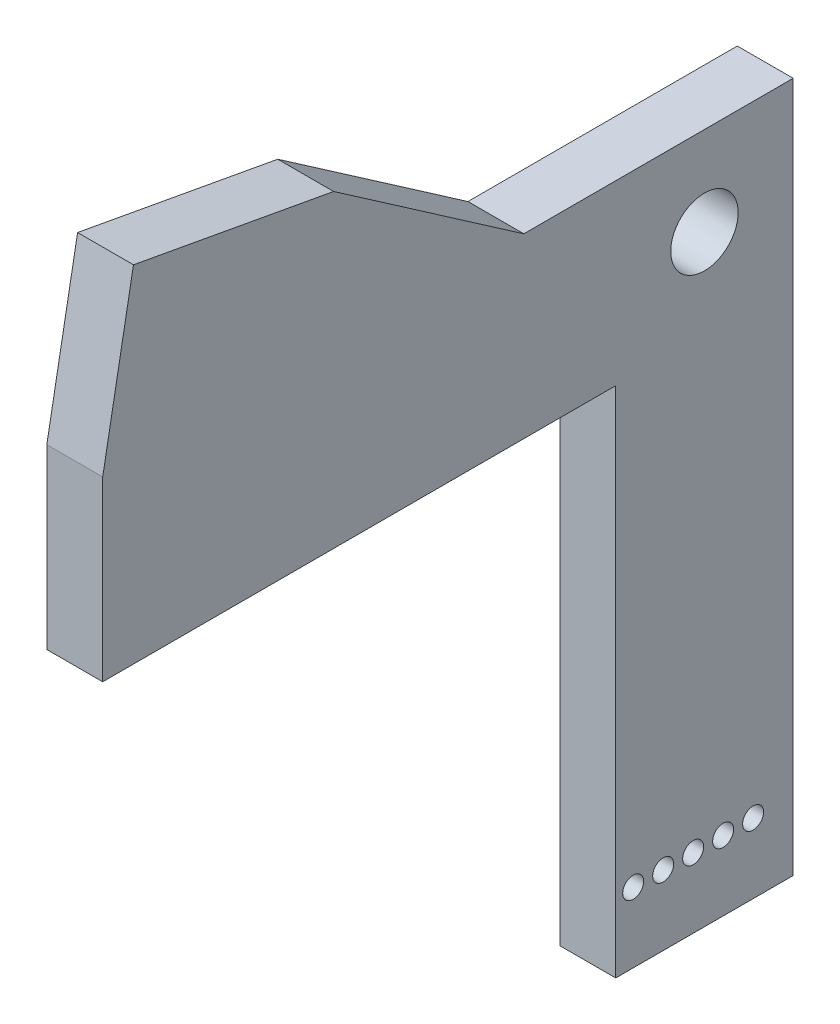
SolidWorks part; units mm, degrees
material "Hardboard"
ref_plane "Front Plane" through (0, 0, 0) normal (0, 0, 1) x (1, 0, 0)
ref_plane "Top Plane" through (0, 0, 0) normal (0, 1, 0) x (1, 0, 0)
ref_plane "Right Plane" through (0, 0, 0) normal (1, 0, 0) x (0, 0, -1)
sketch "Sketch1" plane through (0, 0, 0) normal (1, 0, 0) x (0, 0, -1)
  line L0 (-43.0661, 6.35) -> (6.35, 6.35)
  line L1 (6.35, 6.35) -> (6.35, -43.0661)
  line L2 (6.35, -43.0661) -> (-6.35, -43.0661)
  line L3 (-6.35, -43.0661) -> (-6.35, -6.35)
  line L4 (-6.35, -6.35) -> (-43.0661, -6.35)
  line L5 (-43.0661, -6.35) -> (-43.0661, 6.35)
  line L6 (-6.35, -6.35) -> (6.35, 6.35) construction
  line L7 (-43.0661, 6.35) -> (-40.8645, 18.3959)
  line L8 (-40.8645, 18.3959) -> (-26.5392, 15.7776)
  line L9 (-26.5392, 15.7776) -> (-12.928, 6.35)
  circle A0 centre (0, 0) radius 2.413
  circle A1 centre (-5.1, -38.0661) radius 0.75
  circle A2 centre (-2.9545, -38.0661) radius 0.75
  circle A3 centre (-0.8091, -38.0661) radius 0.75
  circle A4 centre (1.3364, -38.0661) radius 0.75
  circle A5 centre (3.4818, -38.0661) radius 0.75
  dimension "D1" = 4.826
  dimension "D2" = 1.5
  dimension "D3" = 1.25
  dimension "D4" = 5
  dimension "D5" = 5
extrude "Boss-Extrude1" add sketch "Sketch1" along normal mid plane 4 contours L9 L8 L7 L0 | L4 L6 A0 L0 L5 | L6 L3 L2 L1 A0 A5 A4 A3 A2 A1
